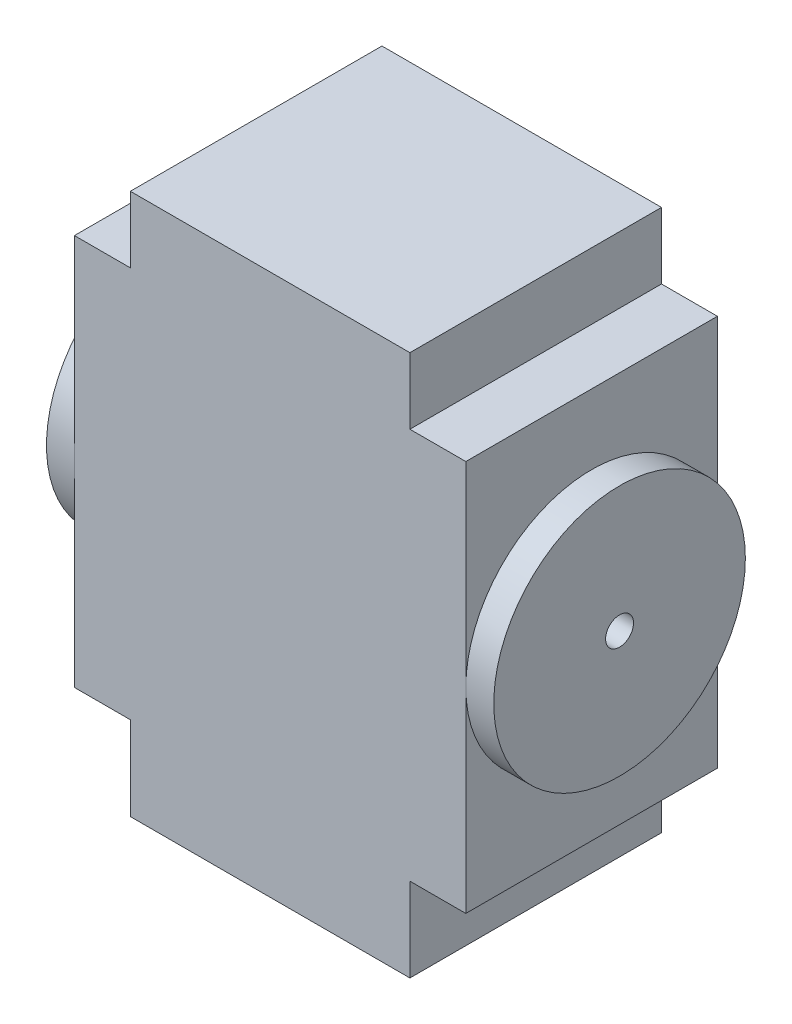
SolidWorks part; units mm, degrees
ref_plane "前视基准面" through (0, 0, 0) normal (0, 0, 1) x (1, 0, 0)
ref_plane "上视基准面" through (0, 0, 0) normal (0, 1, 0) x (1, 0, 0)
ref_plane "右视基准面" through (0, 0, 0) normal (1, 0, 0) x (0, 0, -1)
other "Configuration Table"
sketch "草图4" plane through (0, 0, 0) normal (0, 0, 1) x (1, 0, 0)
  line L1 (-2.5, -5) -> (2.5, -5)
  line L2 (-2.5, -5) -> (-2.5, 5)
  line L3 (-2.5, 5) -> (2.5, 5)
  line L4 (2.5, -5) -> (2.5, 5)
  line L5 (-2.5, -5) -> (2.5, 5) construction
  line L6 (-2.5, 5) -> (2.5, -5) construction
  point P0 (0, 0)
  dimension "D1" = 5
  dimension "D2" = 10
extrude "凸台-拉伸2" add sketch "草图4" along normal blind 4.5
sketch "草图5" plane through (2.5, 0, 0) normal (1, 0, 0) x (0, 0, -1)
  line L0 (0, -5) -> (0, 5) construction
  line L1 (-4.5, -3.5) -> (0, -3.5)
  line L2 (-4.5, -3.5) -> (-4.5, 3.5)
  line L3 (-4.5, 3.5) -> (0, 3.5)
  line L4 (0, -3.5) -> (0, 3.5)
  line L5 (-4.5, -3.5) -> (0, 3.5) construction
  line L6 (-4.5, 3.5) -> (0, -3.5) construction
  line L7 (-4.5, 5) -> (0, 5) construction
  point P0 (-2.25, 0)
  dimension "D1" = 7
  dimension "D2" = 4.5
  dimension "D3" = 1.5
extrude "凸台-拉伸3" add sketch "草图5" along normal blind 1
sketch "草图6" plane through (-2.5, 0, 0) normal (-1, 0, 0) x (0, 0, 1)
  line L0 (0, 5) -> (0, -5) construction
  line L1 (4.5, -3.5) -> (0, -3.5)
  line L2 (4.5, -3.5) -> (4.5, 3.5)
  line L3 (4.5, 3.5) -> (0, 3.5)
  line L4 (0, -3.5) -> (0, 3.5)
  line L5 (4.5, -3.5) -> (0, 3.5) construction
  line L6 (4.5, 3.5) -> (0, -3.5) construction
  line L7 (4.5, 5) -> (0, 5) construction
  point P0 (2.25, 0)
  dimension "D1" = 7
  dimension "D2" = 1.5
extrude "凸台-拉伸4" add sketch "草图6" along normal blind 1
sketch "草图7" plane through (3.5, 0, 0) normal (1, 0, 0) x (0, 0, -1)
  circle A0 centre (-2.25, 0) radius 2.25
extrude "凸台-拉伸5" add sketch "草图7" along normal blind 0.5
mirror "镜向1" about plane through (0, 0, 0) normal (1, 0, 0) of "凸台-拉伸5"
sketch "草图8" plane through (4, 0, 0) normal (1, 0, 0) x (0, 0, -1)
  circle A0 centre (-2.25, 0) radius 0.25
  dimension "D1" = 0.5
extrude "切除-拉伸1" cut sketch "草图8" against normal up to vertex (0.5 mm away)
sketch "草图9" plane through (-4, 0, 0) normal (-1, 0, 0) x (0, 0, 1)
  circle A0 centre (2.25, 0) radius 0.25
  dimension "D1" = 0.5
extrude "切除-拉伸2" cut sketch "草图9" against normal up to vertex (0.5 mm away)
scale "缩放比例1" bodies to scale 113 scale about centroid uniform scaling yes scale factor 3.181818
scale "缩放比例2" bodies to scale 114 scale about centroid uniform scaling yes scale factor 2.454545
scale "缩放比例3" bodies to scale 115 scale about centroid uniform scaling yes scale factor 0.771429
scale "缩放比例4" scale about centroid uniform scaling yes scale factor 0.407393
sketch "草图10" plane through (0, 0, -3.2725) normal (0, 0, -1) x (-1, 0, 0)
  line L0 (-6.1362, 8.5906) -> (-6.1362, 12.2723) construction
  line L1 (-6.1362, 11.5023) -> (8.0764, 11.5023)
  line L2 (-6.1362, 11.5023) -> (-6.1362, 14.7071)
  line L3 (-6.1362, 14.7071) -> (8.0764, 14.7071)
  line L4 (8.0764, 11.5023) -> (8.0764, 14.7071)
  line L5 (-6.1362, 12.2723) -> (6.1362, 12.2723) construction
  dimension "D1" = 0.77
extrude "切除-拉伸3" cut sketch "草图10" against normal through all
